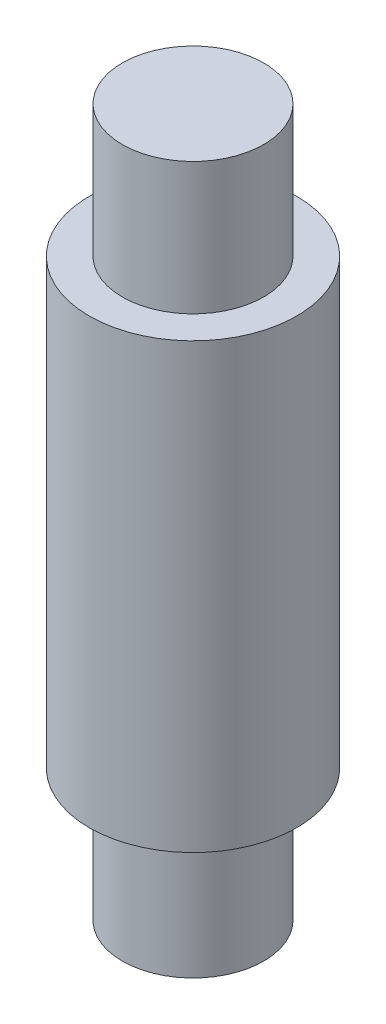
SolidWorks part; units mm, degrees
ref_plane "Front Plane" through (0, 0, 0) normal (0, 0, 1) x (1, 0, 0)
ref_plane "Top Plane" through (0, 0, 0) normal (0, 1, 0) x (1, 0, 0)
ref_plane "Right Plane" through (0, 0, 0) normal (1, 0, 0) x (0, 0, -1)
sketch "Sketch1" plane through (0, 0, 0) normal (0, 0, 1) x (1, 0, 0)
  line L0 (0, 0) -> (15, 0)
  line L1 (15, 0) -> (15, 28)
  line L2 (15, 28) -> (22, 28)
  line L4 (15, 150) -> (0, 150)
  line L5 (0, 150) -> (0, 0)
  line L6 (15, 150) -> (15, 122)
  line L7 (15, 122) -> (22, 122)
  line L8 (22, 122) -> (22, 28)
  dimension "D1" = 150
  dimension "D2" = 28
  dimension "D3" = 28
  dimension "D4" = 22
  dimension "D5" = 15
revolve "Revolve1" add sketch "Sketch1" angle 360 about L5
